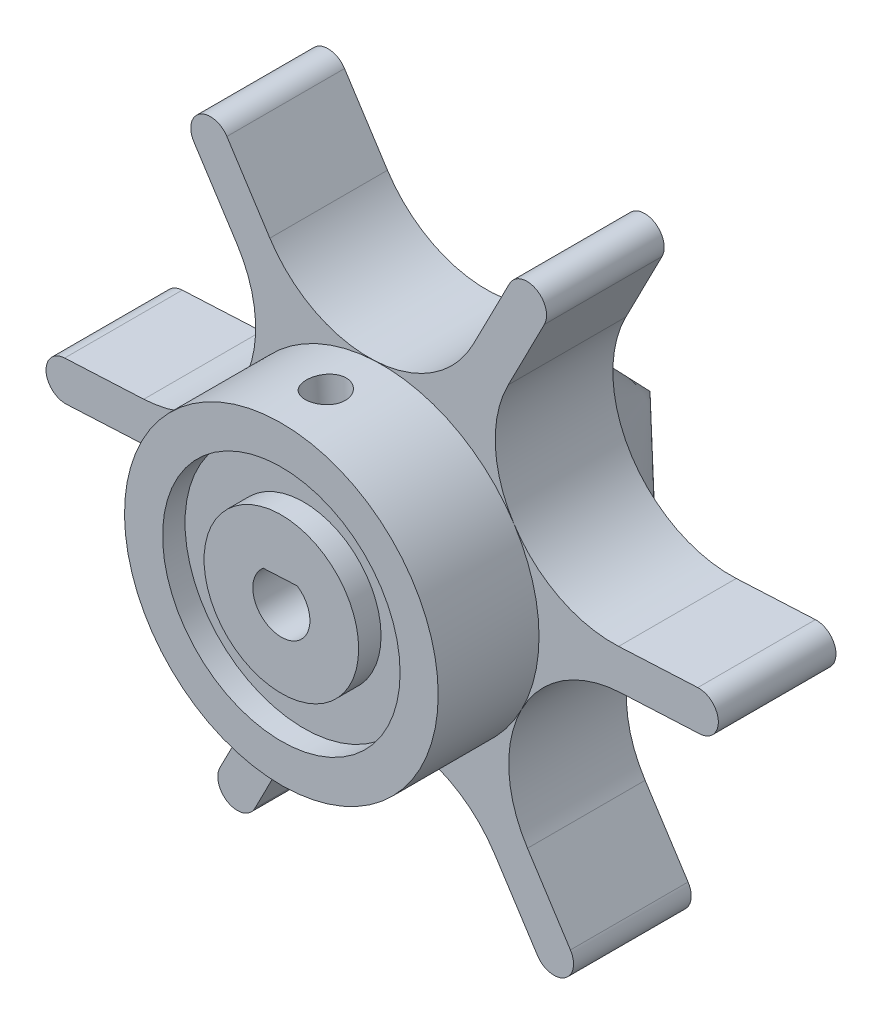
SolidWorks part; units mm, degrees
ref_plane "Front Plane" through (0, 0, 0) normal (0, 0, 1) x (1, 0, 0)
ref_plane "Top Plane" through (0, 0, 0) normal (0, 1, 0) x (1, 0, 0)
ref_plane "Right Plane" through (0, 0, 0) normal (1, 0, 0) x (0, 0, -1)
sketch "Sketch1" plane through (0, 0, 0) normal (0, 0, 1) x (1, 0, 0)
  line L0 (-33.6058, 45.6534) -> (-25.9397, 33.7658)
  line L1 (-30.6644, 47.5503) -> (-56.5119, -2.781) construction
  line L2 (-56.5119, -2.781) -> (-25.8475, -50.3313) construction
  line L3 (-25.8475, -50.3313) -> (30.6644, -47.5503) construction
  line L4 (30.6644, -47.5503) -> (56.5119, 2.781) construction
  line L5 (56.5119, 2.781) -> (25.8475, 50.3313) construction
  line L6 (25.8475, 50.3313) -> (-30.6644, 47.5503) construction
  line L7 (-27.723, 49.4471) -> (-20.0569, 37.5596)
  line L8 (22.7341, 51.9302) -> (16.2722, 39.3474)
  line L9 (28.961, 48.7324) -> (22.4991, 36.1496)
  line L10 (56.3399, 6.2768) -> (42.2119, 5.5815)
  line L11 (56.684, -0.7147) -> (42.556, -1.41)
  line L12 (33.6058, -45.6534) -> (25.9397, -33.7658)
  line L13 (27.723, -49.4471) -> (20.0569, -37.5596)
  line L14 (-22.7341, -51.9302) -> (-16.2722, -39.3474)
  line L15 (-28.961, -48.7324) -> (-22.4991, -36.1496)
  line L16 (-56.3399, -6.2768) -> (-42.2119, -5.5815)
  line L17 (-56.684, 0.7147) -> (-42.556, 1.41)
  circle A0 centre (41.1797, 26.5562) radius 21 construction
  circle A1 centre (43.5882, -22.3846) radius 21 construction
  circle A2 centre (2.4085, -48.9408) radius 21 construction
  circle A3 centre (-41.1797, -26.5562) radius 21 construction
  circle A4 centre (-43.5882, 22.3846) radius 21 construction
  circle A5 centre (-2.4085, 48.9408) radius 21 construction
  circle A6 centre (0, 0) radius 49 construction
  circle A7 centre (-30.6644, 47.5503) radius 3.5
  circle A8 centre (25.8475, 50.3313) radius 3.5
  circle A9 centre (56.5119, 2.781) radius 3.5
  circle A10 centre (30.6644, -47.5503) radius 3.5
  circle A11 centre (-25.8475, -50.3313) radius 3.5
  circle A12 centre (-56.5119, -2.781) radius 3.5
  arc A13 (-42.556, 1.41) -> (-25.9397, 33.7658) centre (-43.5882, 22.3846) ccw
  arc A14 (-20.0569, 37.5596) -> (16.2722, 39.3474) centre (-2.4085, 48.9408) ccw
  arc A15 (22.4991, 36.1496) -> (42.2119, 5.5815) centre (41.1797, 26.5562) ccw
  arc A16 (42.556, -1.41) -> (25.9397, -33.7658) centre (43.5882, -22.3846) ccw
  arc A17 (20.0569, -37.5596) -> (-16.2722, -39.3474) centre (2.4085, -48.9408) ccw
  arc A18 (-22.4991, -36.1496) -> (-42.2119, -5.5815) centre (-41.1797, -26.5562) ccw
  point P25 (0, 0)
  point P36 (0, 0)
  point P60 (0, 0)
  point P77 (0, 0)
  dimension "D2" = 42
  dimension "D4" = 7
  dimension "D1" = 6
  dimension "D3" = 6
  dimension "D5" = 6
  dimension "D6" = 6
extrude "Boss-Extrude1" add sketch "Sketch1" along normal blind 21 contours A18 L15 A11 L14 A17 L13 A10 L12 A16 L11 A9 L10 A15 L9 A8 L8 A14 L7 A7 L0 A13 L17 A12 L16 | A12 | A7 | A8 | A9 | A10 | A11
ref_plane "Plane1" through (0, 0, 0) normal (0.0492, -0.9988, 0) x (-0.9988, -0.0492, 0)
sketch "Sketch3" plane through (0, 0, 0) normal (0.0492, -0.9988, 0) x (-0.9988, -0.0492, 0)
  line L0 (0, 0) -> (-28, 0)
  line L1 (-28, 0) -> (0, 26.8135)
  line L2 (0, 26.8135) -> (0, 0)
  dimension "D1" = 28
revolve "Revolve1" add sketch "Sketch3" angle 360 about L2
sketch "Sketch4" plane through (0, 0, 21) normal (0, 0, 1) x (1, 0, 0)
  circle A0 centre (0, 0) radius 28
extrude "Boss-Extrude2" add sketch "Sketch4" along normal blind 18
sketch "Sketch5" plane through (0, 0, 39) normal (0, 0, 1) x (1, 0, 0)
  line L0 (-3.231, 3.946) -> (2.828, 4.2441)
  line L1 (56.3399, 6.2768) -> (42.2119, 5.5815) construction
  circle A0 centre (0, 0) radius 5.1
  circle A1 centre (0, 0) radius 4.1 construction
  dimension "D1" = 10.2
  dimension "D2" = 8.2
sketch "Sketch6" plane through (0, 0, 39) normal (0, 0, 1) x (1, 0, 0)
  circle A0 centre (0, 0) radius 17.5 construction
  circle A1 centre (0, 0) radius 21.2
  circle A2 centre (0, 0) radius 13.8
  dimension "D1" = 35
  dimension "D2" = 3.7
  dimension "D3" = 3.7
extrude "Cut-Extrude1" cut sketch "Sketch6" against normal blind 4 contours A2 | A1
extrude "Cut-Extrude2" cut sketch "Sketch5" against normal blind 20 contours L0 A0
sketch "Sketch7" plane through (-0.2015, 4.095, 0) normal (0.0492, -0.9988, 0) x (0.9988, 0.0492, 0)
  line L0 (28, 39) -> (-28, 39) construction
  circle A0 centre (0, 29.7) radius 1.75
  point P4 (0, 0)
  dimension "D2" = 3.5
  dimension "D1" = 9.3
extrude "Cut-Extrude3" cut sketch "Sketch7" against normal through all and the other way through all
ref_plane "Plane2" through (-1.3763, 27.9662, 0) normal (-0.0492, 0.9988, 0) x (0.9988, 0.0492, 0)
sketch "Sketch8" plane through (-1.3763, 27.9662, 0) normal (-0.0492, 0.9988, 0) x (0.9988, 0.0492, 0)
  circle A0 centre (0, -29.7) radius 3.5
  dimension "D1" = 7
extrude "Cut-Extrude4" cut sketch "Sketch8" against normal blind 5.5
ref_plane "Plane5" through (1.3763, -27.9662, 0) normal (0.0492, -0.9988, 0) x (-0.9988, -0.0492, 0)
